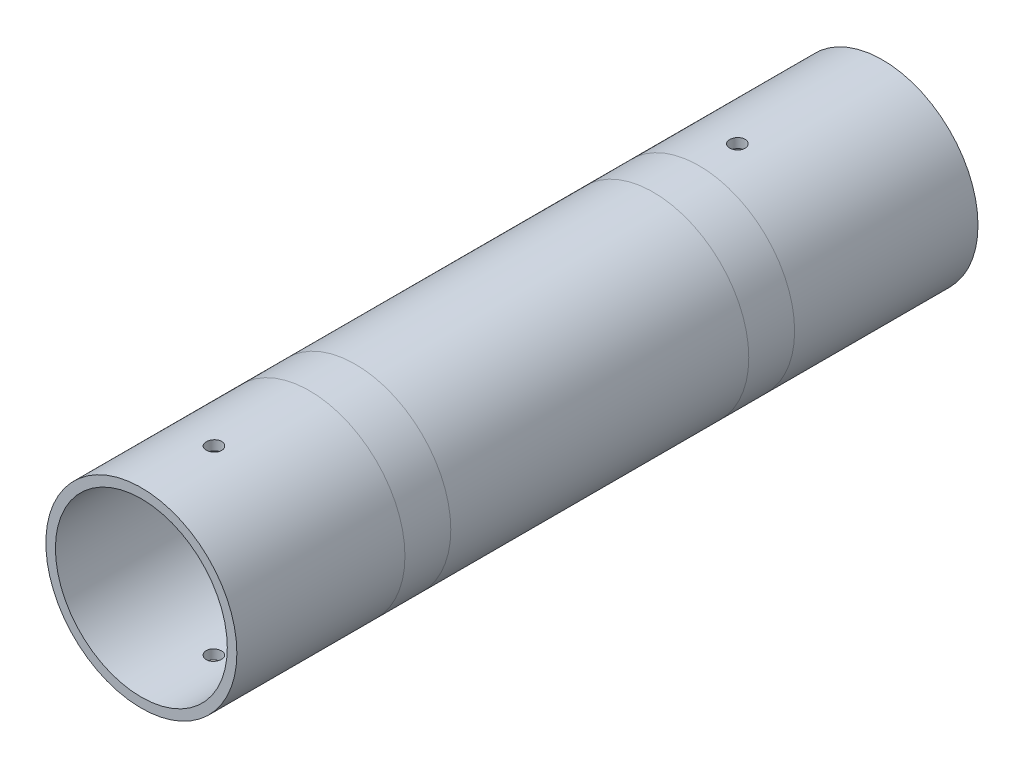
SolidWorks part; units mm, degrees
material "6061 Alloy"
ref_plane "Front Plane" through (0, 0, 0) normal (0, 0, 1) x (1, 0, 0)
ref_plane "Top Plane" through (0, 0, 0) normal (0, 1, 0) x (1, 0, 0)
ref_plane "Right Plane" through (0, 0, 0) normal (1, 0, 0) x (0, 0, -1)
sketch "Sketch1" plane through (0, 0, 0) normal (0, 0, 1) x (1, 0, 0)
  circle A0 centre (0, 0) radius 25
  circle A1 centre (0, 0) radius 22.5
  dimension "D1" = 50
  dimension "D2" = 45
extrude "Boss-Extrude1" add sketch "Sketch1" against normal blind 194
ref_plane "B1" through (0, 0, -50) normal (0, 0, 1) x (1, 0, 0)
ref_plane "B2" through (0, 0, -140) normal (0, 0, 1) x (1, 0, 0)
sketch "Sketch8" plane through (0, 0, 0) normal (0, 1, 0) x (1, 0, 0)
  line L0 (-27.5, 50) -> (27.5, 50) construction
  line L1 (-30, 56) -> (30, 56)
  line L2 (-30, 56) -> (-30, 44)
  line L3 (-30, 44) -> (30, 44)
  line L4 (30, 56) -> (30, 44)
  line L5 (-30, 56) -> (30, 44) construction
  line L6 (-30, 44) -> (30, 56) construction
  point P0 (0, 50)
  dimension "D1" = 60
split line "Split Line4"
sketch "Sketch9" plane through (0, 0, 0) normal (0, 1, 0) x (1, 0, 0)
  line L0 (-27.5, 140) -> (27.5, 140) construction
  line L1 (-30, 146) -> (30, 146)
  line L2 (-30, 146) -> (-30, 134)
  line L3 (-30, 134) -> (30, 134)
  line L4 (30, 146) -> (30, 134)
  line L5 (-30, 146) -> (30, 134) construction
  line L6 (-30, 134) -> (30, 146) construction
  point P0 (0, 140)
  dimension "D1" = 60
split line "Split Line5"
sketch "Sketch3" plane through (0, 0, 0) normal (0, 1, 0) x (1, 0, 0)
  line L0 (-38.8703, 56) -> (48.5445, 56)
  line L1 (-38.8703, 44) -> (48.5445, 44)
  line L2 (-27.5, 50) -> (27.5, 50) construction
  dimension "Bearing_Width" = 12
  dimension "Bearing_Width_Half" = 6
split line "B1 Split Line" [suppressed]
sketch "Sketch5" plane through (0, 0, 0) normal (0, 1, 0) x (1, 0, 0)
  line L0 (-38.3548, 146) -> (55.3733, 146)
  line L1 (-38.3548, 134) -> (55.3733, 134)
  line L2 (-27.5, 140) -> (27.5, 140) construction
  dimension "D1" = 6
  dimension "D2" = 6
split line "B2 Split Line" [suppressed]
sketch "Sketch10" plane through (0, 0, 0) normal (0, 1, 0) x (1, 0, 0)
  line L0 (25, 146) -> (-25, 146) construction
  line L2 (-25, 44) -> (25, 44) construction
  circle A0 centre (0, 156) radius 2
  circle A1 centre (0, 19) radius 2
  dimension "D1" = 4
  dimension "D3" = 4
  dimension "D2" = 10
  dimension "D5" = 25
extrude "Cut-Extrude1" cut sketch "Sketch10" against normal through all both and the other way through all
equation "\"Lc\"= 500mm"
equation "\"BW\"= 20"
